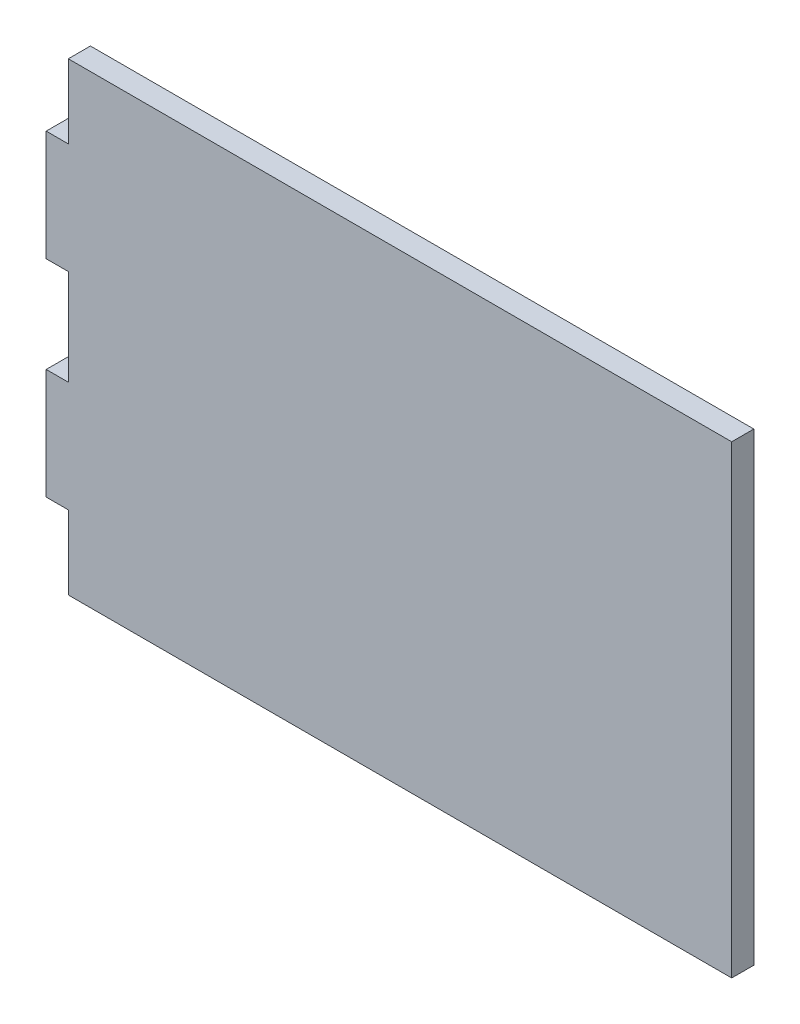
SolidWorks part; units mm, degrees
ref_plane "Front Plane" through (0, 0, 0) normal (0, 0, 1) x (1, 0, 0)
ref_plane "Top Plane" through (0, 0, 0) normal (0, 1, 0) x (1, 0, 0)
ref_plane "Right Plane" through (0, 0, 0) normal (1, 0, 0) x (0, 0, -1)
sketch "Sketch1" plane through (0, 0, 0) normal (0, 0, 1) x (1, 0, 0)
  line L0 (-45, 0) -> (45, 0) construction
  line L1 (-45, -31.5) -> (45, -31.5)
  line L2 (-45, -31.5) -> (-45, 31.5)
  line L3 (-45, 31.5) -> (45, 31.5)
  line L4 (45, -31.5) -> (45, 31.5)
  line L5 (-45, -31.5) -> (45, 31.5) construction
  line L6 (-45, 31.5) -> (45, -31.5) construction
  line L7 (-45, -6.5) -> (-48, -6.5)
  line L8 (-45, 21.5) -> (-48, 21.5)
  line L9 (-45, 21.5) -> (-45, 6.5)
  line L10 (-45, 6.5) -> (-48, 6.5)
  line L11 (-48, 21.5) -> (-48, 6.5)
  line L16 (-48, -21.5) -> (-48, -6.5)
  line L17 (-45, -21.5) -> (-48, -21.5)
  line L18 (-45, -21.5) -> (-45, -6.5)
  point P0 (0, 0)
  dimension "D1" = 90
  dimension "D2" = 63
  dimension "D3" = 15
  dimension "D4" = 13
  dimension "D5" = 3
extrude "Boss-Extrude1" add sketch "Sketch1" along normal mid plane 3 contours L1 L4 L3 L2 | L8 L11 L10 L2 | L17 L2 L7 L16
